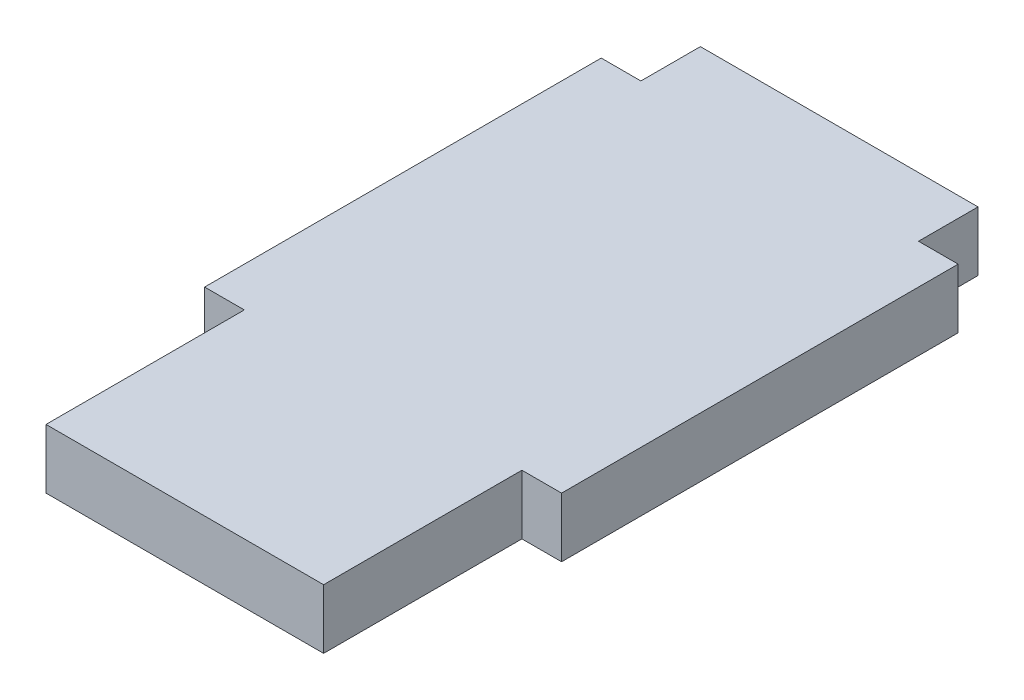
SolidWorks part; units mm, degrees
ref_plane "Спереди" through (0, 0, 0) normal (0, 0, 1) x (1, 0, 0)
ref_plane "Сверху" through (0, 0, 0) normal (0, 1, 0) x (1, 0, 0)
ref_plane "Справа" through (0, 0, 0) normal (1, 0, 0) x (0, 0, -1)
other "Configuration Table"
sketch "Эскиз1" plane through (0, 0, 0) normal (0, 1, 0) x (1, 0, 0)
  line L1 (-7, -15) -> (7, -15)
  line L2 (-9, -8) -> (-9, 12)
  line L3 (-7, 15) -> (7, 15)
  line L4 (9, -8) -> (9, 12)
  line L5 (-7, -11.6667) -> (7.2, 12) construction
  line L6 (-7.2, 12) -> (7, -11.6667) construction
  line L9 (-9, 12) -> (-7, 12)
  line L10 (-7, 15) -> (-7, 12)
  line L13 (9, 12) -> (7, 12)
  line L14 (7, 15) -> (7, 12)
  line L17 (-9, -8) -> (-7, -8)
  line L18 (-7, -15) -> (-7, -8)
  line L21 (9, -8) -> (7, -8)
  line L22 (7, -15) -> (7, -8)
  point P0 (0, 0)
  dimension "D2" = 30
  dimension "D3" = 2
  dimension "D4" = 3
  dimension "D5" = 2
  dimension "D6" = 3
  dimension "D7" = 2
  dimension "D8" = 2
  dimension "D9" = 7
  dimension "D10" = 7
extrude "Бобышка-Вытянуть1" add sketch "Эскиз1" along normal blind 3
sketch "Эскиз2" plane through (0, 0, 15) normal (0, 0, 1) x (1, 0, 0)
  line L4 (-7, 0) -> (7, 0)
  line L5 (7, 0) -> (7, 3)
  line L6 (7, 3) -> (-7, 3)
  line L7 (-7, 3) -> (-7, 0)
  line L8 (-7, 0) -> (7, 0)
  line L9 (7, 0) -> (7, 3)
  line L10 (7, 3) -> (-7, 3)
  line L11 (-7, 3) -> (-7, 0)
  dimension "D1" = 0
extrude "Бобышка-Вытянуть2" add sketch "Эскиз2" along normal blind 3
